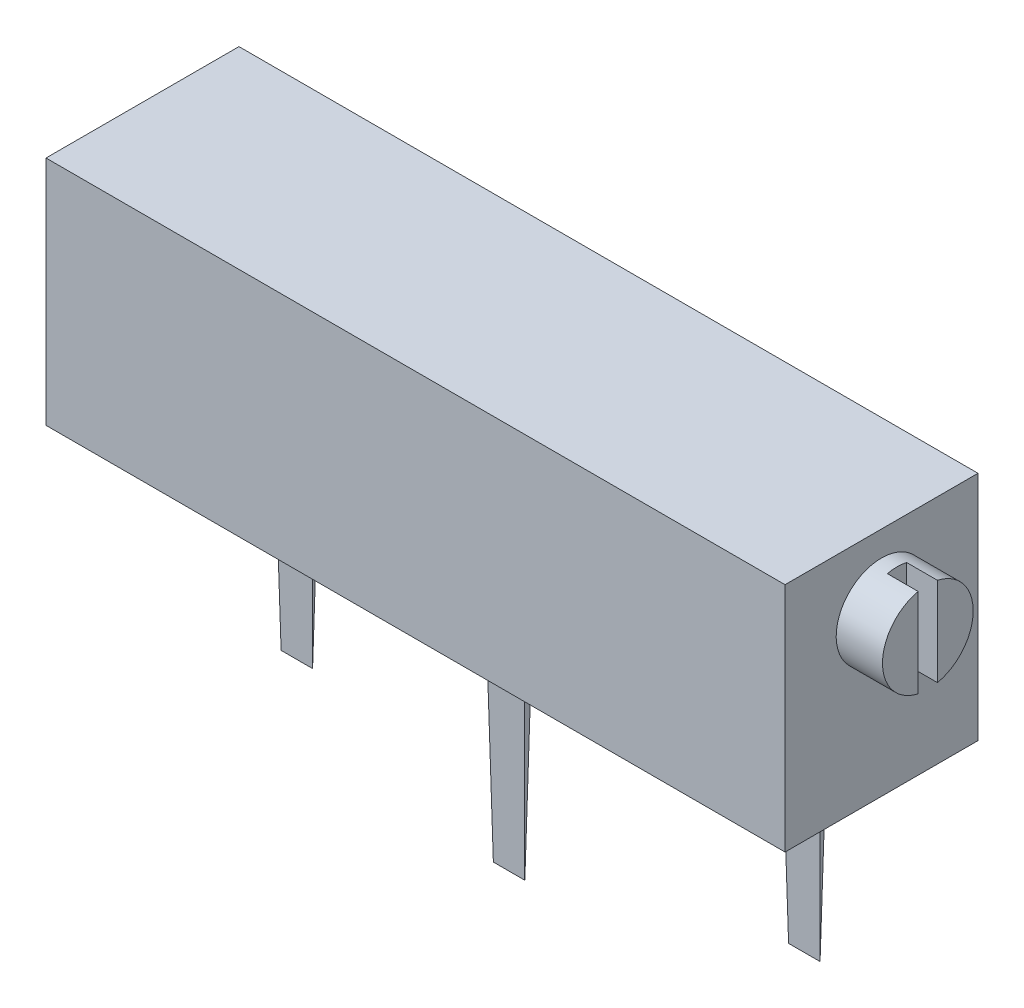
SolidWorks part; units mm, degrees
ref_plane "Front Plane" through (0, 0, 0) normal (0, 0, 1) x (1, 0, 0)
ref_plane "Top Plane" through (0, 0, 0) normal (0, 1, 0) x (1, 0, 0)
ref_plane "Right Plane" through (0, 0, 0) normal (1, 0, 0) x (0, 0, -1)
sketch "Sketch1" plane through (0, 0, 0) normal (0, 1, 0) x (1, 0, 0)
  line L1 (0, 0) -> (19.15, 0)
  line L2 (0, 0) -> (0, 5)
  line L3 (0, 5) -> (19.15, 5)
  line L4 (19.15, 0) -> (19.15, 5)
  dimension "D1" = 19.15
  dimension "D2" = 5
extrude "Boss-Extrude1" add sketch "Sketch1" along normal blind 6
sketch "Sketch3" plane through (19.15, 0, 0) normal (1, 0, 0) x (0, 0, -1)
  line L0 (0, 0) -> (5, 0) construction
  line L1 (0.492, 3) -> (4.3453, 3) construction
  line L2 (0, 6) -> (5, 6) construction
  circle A0 centre (2.5, 4.175) radius 1.175
  point P4 (2.5, 0)
  dimension "D1" = 2.35
  dimension "D2" = 3
extrude "Boss-Extrude2" add sketch "Sketch3" along normal blind 1.2 separate body
sketch "Sketch4" plane through (20.35, 0, 0) normal (1, 0, 0) x (0, 0, -1)
  line L0 (0, 6) -> (5, 6) construction
  line L1 (2.25, 5.35) -> (2.75, 5.35)
  line L2 (2.25, 5.35) -> (2.25, 3)
  line L3 (2.25, 3) -> (2.75, 3)
  line L4 (2.75, 5.35) -> (2.75, 3)
  circle A1 centre (2.5, 4.175) radius 1.175 construction
  point P8 (2.5, 6)
  point P9 (2.5, 5.35)
  dimension "D1" = 0.5
extrude "Cut-Extrude1" cut sketch "Sketch4" against normal blind 0.8
sketch "Sketch5" plane through (0, 0, 0) normal (0, -1, 0) x (1, 0, 0)
  line L0 (2.5, -3.6) -> (3.5, -3.4) construction
  line L1 (2.5, -3.6) -> (3.5, -3.6)
  line L2 (2.5, -3.6) -> (2.5, -3.4)
  line L3 (2.5, -3.4) -> (3.5, -3.4)
  line L4 (3.5, -3.6) -> (3.5, -3.4)
  line L13 (3.5, -3.6) -> (2.5, -3.4) construction
  line L14 (19.15, -5) -> (0, -5) construction
  line L15 (0, -5) -> (0, 0) construction
  line L16 (10, -1.6) -> (11, -1.4) construction
  line L17 (10, -1.6) -> (11, -1.6)
  line L18 (10, -1.6) -> (10, -1.4)
  line L19 (10, -1.4) -> (11, -1.4)
  line L20 (11, -1.6) -> (11, -1.4)
  line L21 (11, -1.6) -> (10, -1.4) construction
  line L22 (0, 0) -> (19.15, 0) construction
  line L23 (15.65, -3.6) -> (16.65, -3.4) construction
  line L24 (15.65, -3.6) -> (16.65, -3.6)
  line L25 (15.65, -3.6) -> (15.65, -3.4)
  line L26 (15.65, -3.4) -> (16.65, -3.4)
  line L27 (16.65, -3.6) -> (16.65, -3.4)
  line L28 (16.65, -3.6) -> (15.65, -3.4) construction
  line L29 (19.15, 0) -> (19.15, -5) construction
  point P4 (3, -3.5)
  point P5 (0, 0)
  point P14 (10.5, -1.5)
  point P21 (16.15, -3.5)
  dimension "D1" = 1
  dimension "D2" = 0.2
  dimension "D3" = 1.5
  dimension "D4" = 3
  dimension "D5" = 1
  dimension "D6" = 0.2
  dimension "D7" = 10.5
  dimension "D8" = 1.5
  dimension "D9" = 1
  dimension "D10" = 0.2
  dimension "D11" = 3
  dimension "D12" = 1.5
extrude "Boss-Extrude3" add sketch "Sketch5" along normal blind 5.5 draft 1 separate body
